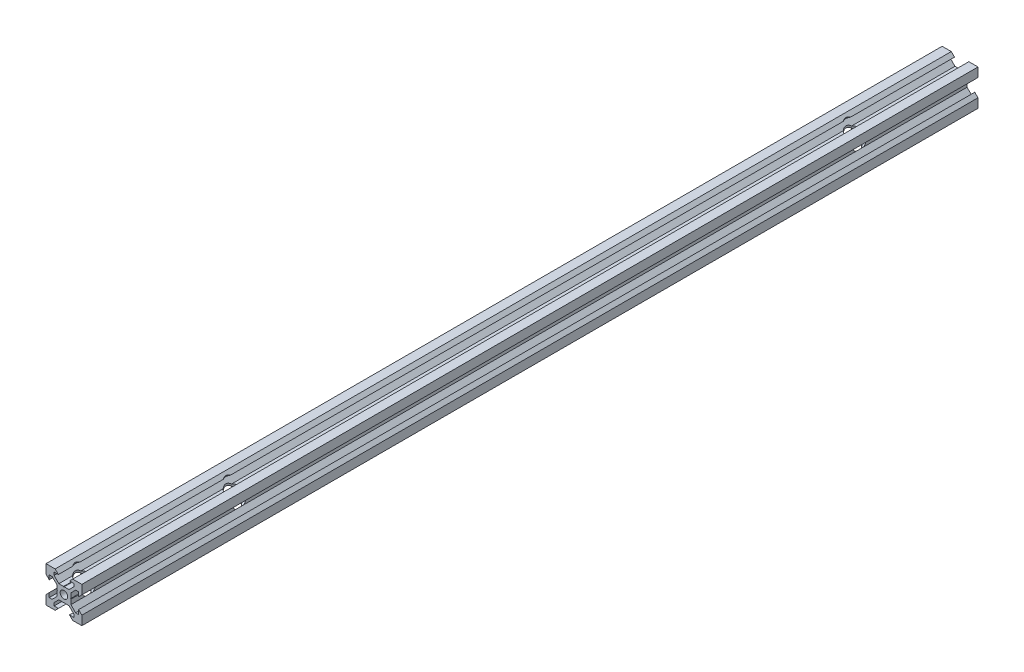
SolidWorks part; units mm, degrees
ref_plane "Front Plane" through (0, 0, 0) normal (0, 0, 1) x (1, 0, 0)
ref_plane "Top Plane" through (0, 0, 0) normal (0, 1, 0) x (1, 0, 0)
ref_plane "Right Plane" through (0, 0, 0) normal (1, 0, 0) x (0, 0, -1)
sketch "Sketch1" plane through (0, 0, 0) normal (0, 0, 1) x (1, 0, 0)
  line L45 (-10, -4.9) -> (-10, -10)
  line L54 (-2.84, -3.9007) -> (2.84, -3.9007)
  line L55 (-3.9007, -2.84) -> (-3.9007, 2.84)
  line L57 (-2.84, 3.9007) -> (2.84, 3.9007)
  line L58 (3.9007, -2.84) -> (3.9007, 2.84)
  line L60 (-3.9007, -3.9007) -> (3.9007, 3.9007) construction
  line L61 (-3.9007, 3.9007) -> (3.9007, -3.9007) construction
  line L62 (-10, -10) -> (-4.9, -10)
  line L63 (-4.9, -10) -> (-3.1, -8.2)
  line L64 (-3.1, -8.2) -> (-5.4993, -8.2)
  line L65 (-5.4993, -8.2) -> (-5.4993, -6.56)
  line L66 (-5.4993, -6.56) -> (-2.84, -3.9007)
  line L68 (-10, -4.9) -> (-8.2, -3.1)
  line L69 (-8.2, -3.1) -> (-8.2, -5.4993)
  line L70 (-8.2, -5.4993) -> (-6.56, -5.4993)
  line L71 (-3.9007, -3.9007) -> (-10, -10) construction
  line L72 (-6.56, -5.4993) -> (-3.9007, -2.84)
  line L73 (0, 0) -> (-3.9007, 0) construction
  line L74 (10, 4.9) -> (10, 10)
  line L75 (5.4993, 6.56) -> (2.84, 3.9007)
  line L76 (6.56, 5.4993) -> (3.9007, 2.84)
  line L77 (8.2, 5.4993) -> (6.56, 5.4993)
  line L78 (8.2, 3.1) -> (8.2, 5.4993)
  line L79 (0, 0) -> (0, -3.9007) construction
  line L80 (5.4993, -8.2) -> (5.4993, -6.56)
  line L81 (3.1, -8.2) -> (5.4993, -8.2)
  line L82 (4.9, -10) -> (3.1, -8.2)
  line L83 (10, -10) -> (4.9, -10)
  line L84 (10, -4.9) -> (10, -10)
  line L85 (10, -4.9) -> (8.2, -3.1)
  line L86 (8.2, -3.1) -> (8.2, -5.4993)
  line L87 (8.2, -5.4993) -> (6.56, -5.4993)
  line L88 (6.56, -5.4993) -> (3.9007, -2.84)
  line L89 (5.4993, -6.56) -> (2.84, -3.9007)
  line L90 (10, 4.9) -> (8.2, 3.1)
  line L91 (10, 10) -> (4.9, 10)
  line L92 (4.9, 10) -> (3.1, 8.2)
  line L93 (3.1, 8.2) -> (5.4993, 8.2)
  line L94 (5.4993, 8.2) -> (5.4993, 6.56)
  line L95 (-10, 10) -> (-4.9, 10)
  line L96 (-3.9007, 3.9007) -> (-10, 10) construction
  line L97 (-6.56, 5.4993) -> (-3.9007, 2.84)
  line L98 (-8.2, 5.4993) -> (-6.56, 5.4993)
  line L99 (-8.2, 3.1) -> (-8.2, 5.4993)
  line L100 (-10, 4.9) -> (-8.2, 3.1)
  line L101 (-5.4993, 6.56) -> (-2.84, 3.9007)
  line L102 (-5.4993, 8.2) -> (-5.4993, 6.56)
  line L103 (-3.1, 8.2) -> (-5.4993, 8.2)
  line L104 (-4.9, 10) -> (-3.1, 8.2)
  line L105 (-10, 4.9) -> (-10, 10)
  circle A1 centre (0, 0) radius 2.1
  dimension "D1" = 4.2
  dimension "D2" = 0.75
  dimension "D4" = 1.8
  dimension "D5" = 1.64
  dimension "D6" = 2.84
  dimension "D7" = 6.2
  dimension "D8" = 20
  dimension "D3" = 0.75
extrude "Boss-Extrude1" add sketch "Sketch1" along normal blind 500
sketch "Sketch2" plane through (0, 0, 0) normal (0, 0, -1) x (-1, 0, 0)
  line L0 (-2.84, 3.9007) -> (2.84, 3.9007) construction
  line L1 (3.9007, 2.84) -> (3.9007, -2.84) construction
  line L2 (2.84, -3.9007) -> (-2.84, -3.9007) construction
  line L3 (-3.9007, -2.84) -> (-3.9007, 2.84) construction
  circle A0 centre (0, 3.9007) radius 0.2
  circle A1 centre (3.9007, 0) radius 0.2
  circle A2 centre (0, -3.9007) radius 0.2
  circle A3 centre (-3.9007, 0) radius 0.2
extrude "Cut-Extrude1" cut sketch "Sketch2" against normal through all
sketch "Sketch3" plane through (-3.9007, 0, 0) normal (-1, 0, 0) x (0, 0, 1)
  line L0 (0, 0) -> (500, 0) construction
  line L1 (500, -0.2) -> (500, 0.2) construction
sketch "Sketch4" plane through (0, -3.9007, 0) normal (0, -1, 0) x (1, 0, 0)
  line L0 (0, 0) -> (0, 500) construction
  line L1 (0.2, 500) -> (-0.2, 500) construction
sketch "Sketch6" plane through (-10, 0, 0) normal (-1, 0, 0) x (0, 0, 1)
  line L0 (0, 0) -> (500, 0) construction
  line L1 (500, 2.84) -> (500, 0.2) construction
  line L2 (500, -0.2) -> (500, -2.84) construction
  line L3 (0, -0.2) -> (0, -2.84) construction
  circle A0 centre (406, 0) radius 3.675
  circle A1 centre (490, 0) radius 3.675
  circle A2 centre (60, 0) radius 3.675
  dimension "D2" = 7.35
  dimension "D4" = 60
  dimension "D1" = 94
  dimension "D3" = 10
extrude "Cut-Extrude2" cut sketch "Sketch6" against normal up to surface (13.9007 mm away) up to face at (3.9007, 1.52, 250)
sketch "Sketch7" plane through (0, 10, 0) normal (0, 1, 0) x (1, 0, 0)
  line L0 (0, 0) -> (0, -500) construction
  line L1 (10, -500) -> (4.9, -500) construction
  line L2 (10, 0) -> (4.9, 0) construction
  circle A0 centre (0, -490) radius 3.675
  circle A2 centre (0, -60) radius 3.675
  circle A3 centre (0, -406) radius 3.675
  dimension "D1" = 7.35
  dimension "D2" = 94
  dimension "D4" = 10
  dimension "D5" = 60
extrude "Cut-Extrude3" cut sketch "Sketch7" against normal up to surface (13.9007 mm away) up to face at (1.52, -3.9007, 250)
